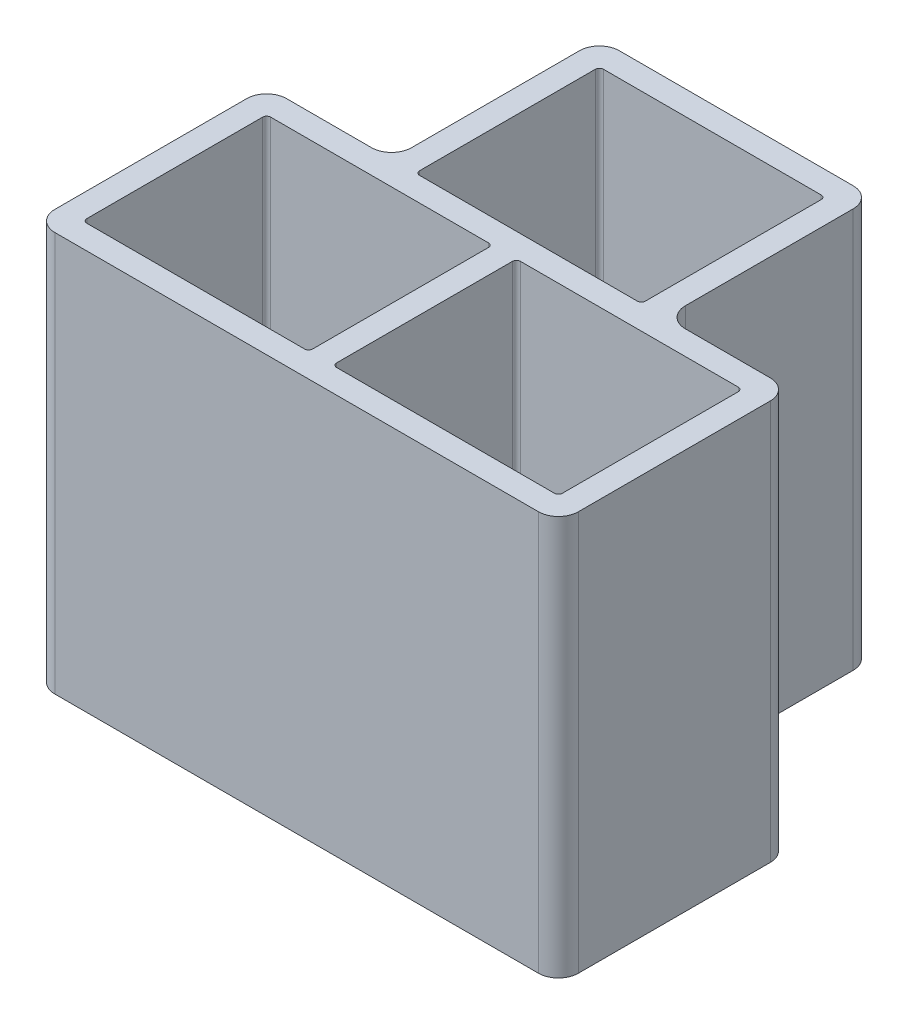
SolidWorks part; units mm, degrees
ref_plane "Plano frontal" through (0, 0, 0) normal (0, 0, 1) x (1, 0, 0)
ref_plane "Plano superior" through (0, 0, 0) normal (0, 1, 0) x (1, 0, 0)
ref_plane "Plano direito" through (0, 0, 0) normal (1, 0, 0) x (0, 0, -1)
sketch "Sketch1" plane through (0, 0, 0) normal (0, 1, 0) x (1, 0, 0)
  line L1 (-6.55, 2.9) -> (6.55, 2.9)
  line L2 (-6.55, 2.9) -> (-6.55, -2.9)
  line L3 (-6.55, -2.9) -> (6.55, -2.9)
  line L4 (6.55, 2.9) -> (6.55, -2.9)
  point P4 (0, 2.9)
  point P6 (-6.55, 0)
  dimension "D1" = 13.1
  dimension "D2" = 5.8
extrude "Boss-Extrude1" add sketch "Sketch1" along normal mid plane 10
sketch "Sketch10" plane through (0, 5, 0) normal (0, 1, 0) x (1, 0, 0)
  line L0 (6.55, 2.9) -> (-6.55, 2.9) construction
  line L1 (-5.95, 2.3) -> (-0.3, 2.3)
  line L2 (-5.95, 2.3) -> (-5.95, -2.3)
  line L3 (-5.95, -2.3) -> (-0.3, -2.3)
  line L4 (5.95, 2.3) -> (5.95, -2.3)
  line L5 (-6.55, 2.9) -> (-6.55, -2.9) construction
  line L6 (-0.3, 2.3) -> (-0.3, -2.3)
  line L7 (0, -3.19) -> (0, 3.19) construction
  line L8 (0.3, 2.3) -> (0.3, -2.3)
  line L9 (0.3, 2.3) -> (5.95, 2.3)
  line L10 (-0.3, 2.3) -> (0.3, 2.3) construction
  line L11 (0.3, -2.3) -> (5.95, -2.3)
  line L12 (-0.3, -2.3) -> (0.3, -2.3) construction
  point P6 (-5.95, 0)
  dimension "D1" = 0.6
  dimension "D2" = 0.6
  dimension "D3" = 0.6
extrude "Cut-Extrude7" cut sketch "Sketch10" against normal offset from surface (6.6 mm away) 3.4 up to face at (0, -5, 0)
sketch "Sketch9" plane through (0, 0, 0) normal (0, 1, 0) x (1, 0, 0)
  line L0 (-5.95, 2.3) -> (-0.3, 2.3) construction
  line L1 (-3.125, 2.3) -> (-3.125, -2.3) construction
  line L4 (-5.95, 2.3) -> (-0.3, 2.3) construction
  line L6 (-5.95, -2.3) -> (-5.95, 2.3) construction
  line L8 (-0.3, -2.3) -> (-5.95, -2.3) construction
  line L11 (0, -3.19) -> (0, 3.19) construction
  circle A0 centre (-4.625, 0) radius 0.75
  circle A2 centre (-1.625, 0) radius 0.75
  circle A3 centre (1.625, 0) radius 0.75
  circle A4 centre (4.625, 0) radius 0.75
  point P17 (-3.125, 0)
  dimension "D1" = 1.5
  dimension "D2" = 1.5
  dimension "D3" = 0.575
extrude "Cut-Extrude6" cut sketch "Sketch9" against normal through all both and the other way through all
sketch "Sketch11" plane through (0, 0, 0) normal (0, 1, 0) x (1, 0, 0)
  line L0 (6.55, 2.9) -> (-6.55, 2.9) construction
  line L1 (-3.425, 2.9) -> (3.425, 2.9)
  line L2 (-2.825, 2.9) -> (-2.825, 7.5)
  line L3 (-2.825, 7.5) -> (2.825, 7.5)
  line L4 (2.825, 2.9) -> (2.825, 7.5)
  line L5 (-0.3, 2.3) -> (-5.95, 2.3) construction
  line L6 (-5.95, 2.3) -> (-5.95, -2.3) construction
  line L7 (-3.425, 2.9) -> (-3.425, 8.1)
  line L8 (-3.425, 8.1) -> (3.425, 8.1)
  line L9 (3.425, 2.9) -> (3.425, 8.1)
  line L11 (-3.425, 2.3) -> (3.425, 2.3) construction
  line L12 (-2.825, 2.9) -> (2.825, 2.9) construction
  line L14 (-3.425, 2.3) -> (-3.425, 8.1) construction
  line L15 (3.425, 2.3) -> (3.425, 8.1) construction
  point P17 (0, 2.9)
  dimension "D1" = 0.6
extrude "Boss-Extrude2" add sketch "Sketch11" along normal up to surface and the other way up to surface contours L1 L9 L8 L7 L2 L3 L4
sketch "Sketch12" plane through (0, -5, 0) normal (0, -1, 0) x (1, 0, 0)
  line L0 (0, -5.5) -> (0, 5.5) construction
  line L1 (-2.825, -2.9) -> (2.825, -2.9)
  line L2 (-2.825, -2.9) -> (-2.825, -7.5)
  line L3 (-2.825, -7.5) -> (2.825, -7.5)
  line L4 (2.825, -2.9) -> (2.825, -7.5)
  line L5 (-4.625, 0) -> (-1.625, 0) construction
  circle A0 centre (-1.5, -5.2) radius 0.75
  circle A1 centre (-1.625, 0) radius 0.75 construction
  circle A2 centre (1.5, -5.2) radius 0.75
  point P9 (-2.825, -5.2)
  dimension "D1" = 3
  dimension "D2" = 3
extrude "Boss-Extrude3" add sketch "Sketch12" against normal up to surface (3.4 mm away) up to face at (-4.625, -1.6, 0.75)
fillet "Filete1" radius 0.5 8 edges at (-6.55, 0, -2.9) (-3.425, 0, -2.9) (-3.425, 0, -8.1) (3.425, 0, -8.1) (6.55, 0, -2.9) (3.425, 0, -2.9) (6.55, 0, 2.9) (-6.55, 0, 2.9)
fillet "Filete2" radius 0.1 12 edges at (-2.825, 1.7, -7.5) (5.95, 1.7, -2.3) (5.95, 1.7, 2.3) (0.3, 1.7, 2.3) (0.3, 1.7, -2.3) (-0.3, 1.7, 2.3) (-5.95, 1.7, 2.3) (-0.3, 1.7, -2.3) (-5.95, 1.7, -2.3) (2.825, 1.7, -7.5) (2.825, 1.7, -2.9) (-2.825, 1.7, -2.9)
